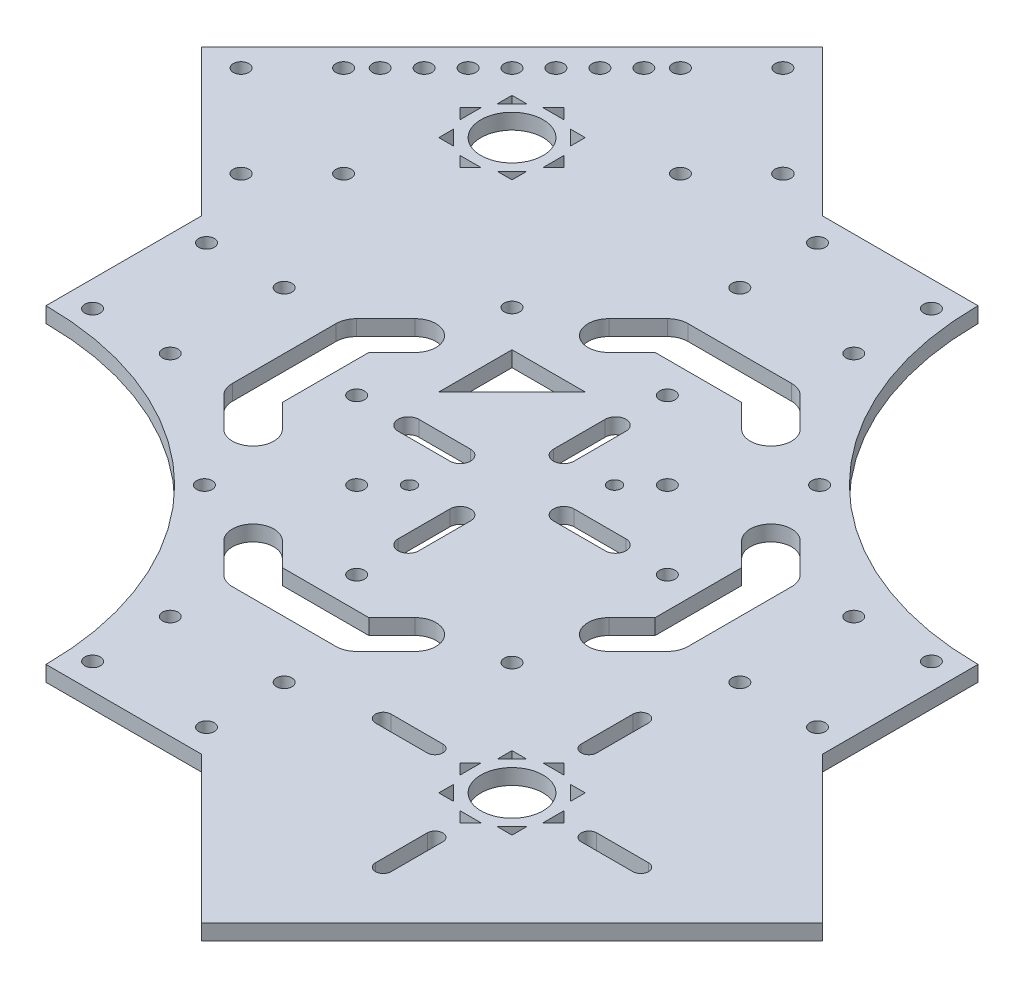
SolidWorks part; units mm, degrees
material "Hexcel AS4C (3000 丝)"
ref_plane "前视基准面" through (0, 0, 0) normal (0, 0, 1) x (1, 0, 0)
ref_plane "上视基准面" through (0, 0, 0) normal (0, 1, 0) x (1, 0, 0)
ref_plane "右视基准面" through (0, 0, 0) normal (1, 0, 0) x (0, 0, -1)
sketch "草图1" plane through (0, 0, 0) normal (0, 1, 0) x (1, 0, 0)
  line L0 (0, 0) -> (0, 75)
  line L1 (0, 0) -> (75, 0)
  line L2 (0, 0) -> (0, -75)
  line L3 (0, 0) -> (-75, 0)
  line L4 (0, 75) -> (15, 75)
  line L5 (0, 75) -> (-15, 75)
  line L6 (75, 0) -> (75, 15)
  line L7 (75, 0) -> (75, -15)
  line L8 (0, -75) -> (15, -75)
  line L9 (0, -75) -> (-15, -75)
  line L10 (-75, 0) -> (-75, -15)
  line L11 (-75, 0) -> (-75, 15)
  line L12 (75, 0) -> (70, 0)
  arc A0 (-75, 15) -> (-15, 75) centre (-75, 75) ccw
  arc A1 (15, 75) -> (75, 15) centre (75, 75) ccw
  arc A2 (75, -15) -> (15, -75) centre (75, -75) ccw
  arc A3 (-15, -75) -> (-75, -15) centre (-75, -75) ccw
  circle A4 centre (-11, 70) radius 1.25
  circle A5 centre (11, 70) radius 1.25
  circle A6 centre (70, -11) radius 1.25
  circle A7 centre (70, 11) radius 1.25
  circle A8 centre (-11, -70) radius 1.25
  circle A9 centre (11, -70) radius 1.25
  circle A10 centre (-70, 11) radius 1.25
  circle A11 centre (-70, -11) radius 1.25
  point P9 (0, 0)
  point P21 (0, 0)
  point P32 (0, 0)
  point P35 (0, 0)
  point P44 (0, 0)
  dimension "D1" = 4
extrude "凸台-拉伸1" add sketch "草图1" along normal blind 3 contours A2 L7 L1 L2 L8 A9 A6 | A3 L9 L2 L3 L10 A11 A8 | A0 L11 L3 L0 L5 A4 A10 | A1 L4 L0 L1 L6 A7 A5
sketch "草图2" plane through (0, 0, 0) normal (0, -1, 0) x (1, 0, 0)
  line L0 (0, 0) -> (-32.5736, -32.5736)
  line L1 (0, 0) -> (32.5736, -32.5736)
  line L2 (-31.4663, 0.3536) -> (-0.3536, 31.4663)
  line L3 (31.4663, -0.3536) -> (-0.3536, 31.4663)
  line L4 (0.3536, -31.4663) -> (31.4663, -0.3536)
  line L5 (0.3536, -31.4663) -> (-31.4663, 0.3536)
  arc A0 (-15, -75) -> (-75, -15) centre (-75, -75) ccw construction
  circle A2 centre (0.3536, -31.4663) radius 1.5
  circle A3 centre (31.4663, -0.3536) radius 1.5
  circle A4 centre (-0.3536, 31.4663) radius 1.5
  circle A5 centre (-31.4663, 0.3536) radius 1.5
  point P12 (-15.5563, -15.5563)
  point P16 (-15.9099, 15.9099)
  point P17 (15.9099, -15.9099)
extrude "切除-拉伸1" cut sketch "草图2" against normal blind 3 contours A3 | A2 | A5 | A4
sketch "草图3" plane through (0, 3, 0) normal (0, 1, 0) x (1, 0, 0)
  line L0 (0.3536, 31.4663) -> (-31.4663, -0.3536)
  line L1 (-15.5563, 15.5563) -> (-22.6274, 22.6274)
  line L2 (-15.5563, 15.5563) -> (-12.0208, 19.0919)
  line L3 (-15.5563, 15.5563) -> (-19.0919, 12.0208)
  line L4 (-19.0919, 12.0208) -> (-22.6274, 22.6274)
  line L5 (-12.0208, 19.0919) -> (-22.6274, 22.6274)
extrude "切除-拉伸2" cut sketch "草图3" against normal blind 3 contours L0 L5 L1 | L4 L0 L1
sketch "草图4" plane through (0, 3, 0) normal (0, 1, 0) x (1, 0, 0)
  line L0 (31.4663, 0.3536) -> (-0.3536, -31.4663)
  line L1 (0, 0) -> (21.2132, -21.2132)
  line L2 (28.2843, -14.1421) -> (14.1421, -28.2843)
  line L3 (14.1421, -28.2843) -> (28.2843, -14.1421) construction
  line L4 (8.4817, -22.6239) -> (22.6239, -8.4817)
  line L5 (19.8025, -33.9447) -> (33.9447, -19.8025)
  arc A0 (8.4817, -22.6239) -> (19.8025, -33.9447) centre (14.1421, -28.2843) ccw
  arc A1 (33.9447, -19.8025) -> (22.6239, -8.4817) centre (28.2843, -14.1421) ccw
  point P9 (21.2132, -21.2132)
extrude "切除-拉伸3" cut sketch "草图4" against normal blind 3
sketch "草图5" plane through (0, 3, 0) normal (0, 1, 0) x (1, 0, 0)
  line L0 (-12.0208, 19.0919) -> (-8.4853, 22.6274)
  line L1 (-8.4853, 22.6274) -> (-22.6274, 22.6274)
  line L2 (-19.0919, 12.0208) -> (-22.6274, 8.4853)
  line L3 (-22.6274, 8.4853) -> (-22.6274, 22.6274)
  line L4 (-12.0208, 19.0919) -> (-22.6274, 22.6274)
  line M28 (-19.0919, 12.0208) -> (-22.6274, 22.6274)
extrude "切除-拉伸4" cut sketch "草图5" against normal blind 10 contours L3 L2 M28 | L4 L0 L1
sketch "草图6" plane through (0, 3, 0) normal (0, 1, 0) x (1, 0, 0)
  line L0 (0, 0) -> (-28.2843, -28.2843)
  line L1 (-28.2843, -28.2843) -> (-35.3553, -21.2132)
  line L2 (0, 0) -> (-22.6274, 22.6274)
  circle A0 centre (-35.3553, -21.2132) radius 1.5
  circle A1 centre (-21.2132, -35.3553) radius 1.5
  circle A2 centre (35.3553, 21.2132) radius 1.5
  circle A3 centre (21.2132, 35.3553) radius 1.5
extrude "切除-拉伸5" cut sketch "草图6" against normal blind 10 contours A1 | A0 | A2 | A3
sketch "草图7" plane through (0, 3, 0) normal (0, 1, 0) x (1, 0, 0)
  circle A0 centre (-29.6985, 29.6985) radius 1.5
  circle A1 centre (29.6985, 29.6985) radius 1.5
  circle A2 centre (29.6985, -29.6985) radius 1.5
  circle A3 centre (-29.6985, -29.6985) radius 1.5
  point P11 (0, 0)
  dimension "D1" = 4
extrude "切除-拉伸8" cut sketch "草图7" against normal blind 10
sketch "草图8" plane through (0, 3, 0) normal (0, 1, 0) x (1, 0, 0)
  circle A0 centre (-11, 55) radius 1.5
  circle A1 centre (11, 55) radius 1.5
  circle A2 centre (55, 11) radius 1.5
  circle A3 centre (55, -11) radius 1.5
  circle A4 centre (11, -55) radius 1.5
  circle A5 centre (-11, -55) radius 1.5
  circle A6 centre (-55, -11) radius 1.5
  circle A7 centre (-55, 11) radius 1.5
  point P21 (0, 0)
  dimension "D1" = 4
extrude "切除-拉伸9" cut sketch "草图8" against normal blind 10
sketch "草图9" plane through (0, 3, 0) normal (0, 1, 0) x (1, 0, 0)
  circle A0 centre (0, 0) radius 15
extrude "切除-拉伸10" cut sketch "草图9" against normal blind 10
sketch "草图11" plane through (0, 3, 0) normal (0, 1, 0) x (1, 0, 0)
  circle A0 centre (-35.3553, -21.2132) radius 1.5
  circle A2 centre (35.3553, 21.2132) radius 1.5
  circle A3 centre (21.2132, 35.3553) radius 1.5
  circle A4 centre (0.3536, 31.4663) radius 1.5
  circle A5 centre (31.4663, 0.3536) radius 1.5
  circle A6 centre (-0.3536, -31.4663) radius 1.5
  circle A7 centre (-31.4663, -0.3536) radius 1.5
  circle A8 centre (-21.2132, -35.3553) radius 1.5
extrude "凸台-拉伸3" add sketch "草图11" against normal blind 3
sketch "草图12" plane through (0, 3, 0) normal (0, 1, 0) x (1, 0, 0)
  line L0 (0, 0) -> (-40, 0)
  line L1 (-40, 0) -> (-40, 10)
  line L2 (-40, 0) -> (-40, -10)
  line L3 (-40, -10) -> (-40, 10) construction
  line L4 (-44, -10) -> (-44, 10)
  line L5 (-36, -10) -> (-36, 10)
  line L6 (-10, 40) -> (10, 40) construction
  line L7 (-10, 44) -> (10, 44)
  line L8 (-10, 36) -> (10, 36)
  line L9 (40, 10) -> (40, -10) construction
  line L10 (44, 10) -> (44, -10)
  line L11 (36, 10) -> (36, -10)
  line L12 (10, -40) -> (-10, -40) construction
  line L13 (10, -44) -> (-10, -44)
  line L14 (10, -36) -> (-10, -36)
  arc A0 (-44, -10) -> (-36, -10) centre (-40, -10) ccw
  arc A1 (-36, 10) -> (-44, 10) centre (-40, 10) ccw
  arc A2 (-10, 44) -> (-10, 36) centre (-10, 40) ccw
  arc A3 (10, 36) -> (10, 44) centre (10, 40) ccw
  arc A4 (44, 10) -> (36, 10) centre (40, 10) ccw
  arc A5 (36, -10) -> (44, -10) centre (40, -10) ccw
  arc A6 (10, -44) -> (10, -36) centre (10, -40) ccw
  arc A7 (-10, -36) -> (-10, -44) centre (-10, -40) ccw
  point P3 (-40, 0)
  point P13 (0, 40)
  point P20 (40, 0)
  point P27 (0, -40)
  point P34 (0, 0)
  dimension "D1" = 4
extrude "切除-拉伸12" cut sketch "草图12" against normal blind 3
sketch "草图14" plane through (0, 3, 0) normal (0, 1, 0) x (1, 0, 0)
  line L0 (22.8277, -8.285) -> (8.285, -22.8277) construction
  line L1 (19.8025, -33.9447) -> (33.9447, -19.8025) construction
  line L2 (8.285, -22.8277) -> (22.8277, -8.285)
  line L3 (22.8277, -8.285) -> (19.8025, -33.9447)
  line L4 (19.8025, -33.9447) -> (33.9447, -19.8025)
  arc A0 (8.285, -22.8277) -> (19.8025, -33.9447) centre (14.1421, -28.2843) ccw
  arc A1 (8.285, -22.8277) -> (19.8025, -33.9447) centre (14.1421, -28.2843) ccw construction
  arc A2 (33.9447, -19.8025) -> (22.8277, -8.285) centre (28.2843, -14.1421) ccw construction
  arc A3 (22.8277, -8.285) -> (32.1857, -7.1522) centre (28.2843, -14.1421) ccw
  circle A4 centre (28.2843, -14.1421) radius 8.005
extrude "凸台-拉伸4" add sketch "草图14" against normal blind 3 contours A3 A4 L3 | L2 A3 L3 | A3 L2 A0 L3 | A3 L3 L4
sketch "草图15" plane through (0, 3, 0) normal (0, 1, 0) x (1, 0, 0)
  circle A0 centre (0, 0) radius 15
extrude "凸台-拉伸5" add sketch "草图15" against normal blind 3
sketch "草图17" plane through (0, 3, 0) normal (0, 1, 0) x (1, 0, 0)
  line L0 (0, 0) -> (0, -20)
  line L1 (0, -20) -> (0, -10) construction
  line L2 (-2, -20) -> (-2, -10)
  line L3 (2, -20) -> (2, -10)
  line L4 (-20, 0) -> (-10, 0) construction
  line L5 (-20, 2) -> (-10, 2)
  line L6 (-20, -2) -> (-10, -2)
  line L7 (0, 20) -> (0, 10) construction
  line L8 (2, 20) -> (2, 10)
  line L9 (-2, 20) -> (-2, 10)
  line L10 (20, 0) -> (10, 0) construction
  line L11 (20, -2) -> (10, -2)
  line L12 (20, 2) -> (10, 2)
  arc A0 (-2, -20) -> (2, -20) centre (0, -20) ccw
  arc A1 (2, -10) -> (-2, -10) centre (0, -10) ccw
  arc A2 (-20, 2) -> (-20, -2) centre (-20, 0) ccw
  arc A3 (-10, -2) -> (-10, 2) centre (-10, 0) ccw
  arc A4 (2, 20) -> (-2, 20) centre (0, 20) ccw
  arc A5 (-2, 10) -> (2, 10) centre (0, 10) ccw
  arc A6 (20, -2) -> (20, 2) centre (20, 0) ccw
  arc A7 (10, 2) -> (10, -2) centre (10, 0) ccw
  point P3 (0, -15)
  point P13 (-15, 0)
  point P20 (0, 15)
  point P27 (15, 0)
  point P33 (0, 0)
  dimension "D1" = 4
extrude "切除-拉伸13" cut sketch "草图17" against normal blind 3 contours L8 A5 L9 A4 | L12 A7 L11 A6 | L3 A1 L2 A0 | L5 A3 L6 A2
sketch "草图18" plane through (0, 3, 0) normal (0, 1, 0) x (1, 0, 0)
  line L0 (0, 0) -> (-32.5736, 32.5736)
  line L1 (-32.5736, 32.5736) -> (-46.7157, 46.7157)
  line L2 (-50.2513, 50.2513) -> (-61.9773, 38.5252)
  line L3 (-46.7157, 46.7157) -> (-50.2513, 50.2513)
  line L4 (-61.9773, 38.5252) -> (-38.5252, 61.9773)
  line L5 (-38.5252, 61.9773) -> (-22.5002, 45.9523)
  line L6 (-61.9773, 38.5252) -> (-45.9523, 22.5002)
  arc A0 (-75, 15) -> (-15, 75) centre (-75, 75) ccw construction
  circle A1 centre (-67.9289, 67.9289) radius 30
  circle A2 centre (-75, 75) radius 60
extrude "凸台-拉伸7" add sketch "草图18" against normal blind 3 contours L4 A1 L2 | L2 A1 L3 | L3 A1 L4 | L6 A2 L1 A1 | L1 A2 L5 A1
sketch "草图19" plane through (0, 3, 0) normal (0, 1, 0) x (1, 0, 0)
  line L0 (-61.9773, 38.5252) -> (-38.5252, 61.9773)
  line L1 (-50.2513, 50.2513) -> (-36.1091, 36.1091)
  line L2 (-36.1091, 36.1091) -> (-43.1802, 29.0381)
  line L3 (-36.1091, 36.1091) -> (-29.0381, 43.1802)
  line L4 (-29.0381, 43.1802) -> (-37.1408, 51.2829)
  line L5 (-37.1408, 51.2829) -> (-51.2829, 37.1408)
  line L6 (-51.2829, 37.1408) -> (-43.1802, 29.0381)
  circle A1 centre (-67.9289, 67.9289) radius 35
  circle A2 centre (-67.9289, 67.9289) radius 45
extrude "切除-拉伸14" cut sketch "草图19" against normal blind 3 contours L1 A2 L4 A1 | L6 A2 L1 A1
sketch "草图21" plane through (0, 3, 0) normal (0, 1, 0) x (1, 0, 0)
  line L0 (-61.9773, 38.5252) -> (-38.5252, 61.9773)
  line L1 (-67.9289, 67.9289) -> (-53.7868, 53.7868)
  line L2 (-82.0711, 82.0711) -> (-75, 75)
  line L3 (-67.9289, 67.9289) -> (-82.0711, 82.0711)
  line L4 (-53.7868, 53.7868) -> (-60.8579, 60.8579)
  line L5 (-82.0711, 82.0711) -> (-75, 75) construction
  line L6 (-81.1872, 82.955) -> (-74.1161, 75.8839)
  line L7 (-82.955, 81.1872) -> (-75.8839, 74.1161)
  line L8 (-60.8579, 60.8579) -> (-53.7868, 53.7868) construction
  line L9 (-59.974, 61.7417) -> (-52.9029, 54.6707)
  line L10 (-61.7417, 59.974) -> (-54.6707, 52.9029)
  arc A0 (-81.1872, 82.955) -> (-82.955, 81.1872) centre (-82.0711, 82.0711) ccw
  arc A1 (-75.8839, 74.1161) -> (-74.1161, 75.8839) centre (-75, 75) ccw
  arc A2 (-59.974, 61.7417) -> (-61.7417, 59.974) centre (-60.8579, 60.8579) ccw
  arc A3 (-54.6707, 52.9029) -> (-52.9029, 54.6707) centre (-53.7868, 53.7868) ccw
  point P2 (-78.5355, 78.5355)
  point P15 (-57.3223, 57.3223)
extrude "切除-拉伸15" cut sketch "草图21" against normal blind 3
pattern_circular "阵列(圆周)1" count 8 over 360 about axis through (-67.9289, 0, -67.9289) along (0, 1, 0) of "切除-拉伸15"
sketch "草图22" plane through (0, 3, 0) normal (0, 1, 0) x (1, 0, 0)
  line L0 (0, 0) -> (9.8995, 9.8995)
  line L1 (0, 0) -> (-9.8995, -9.8995)
  circle A0 centre (9.8995, 9.8995) radius 1.25
  circle A1 centre (-9.8995, -9.8995) radius 1.25
extrude "切除-拉伸17" cut sketch "草图22" against normal blind 3 contours A0 | A1
sketch "草图23" plane through (0, 3, 0) normal (0, 1, 0) x (1, 0, 0)
  circle A0 centre (0, 30) radius 1.5
  circle A1 centre (30, 0) radius 1.5
  circle A2 centre (0, -30) radius 1.5
  circle A3 centre (-30, 0) radius 1.5
  point P13 (0, 0)
  dimension "D1" = 4
extrude "切除-拉伸18" cut sketch "草图23" against normal blind 10
sketch "草图24" plane through (0, 3, 0) normal (0, 1, 0) x (1, 0, 0)
  circle A0 centre (-15, -15) radius 1.5
  circle A1 centre (15, 15) radius 1.5
extrude "切除-拉伸19" cut sketch "草图24" against normal blind 10
sketch "草图25" plane through (0, 3, 0) normal (0, 1, 0) x (1, 0, 0)
  circle A0 centre (-75, 75) radius 60
extrude "切除-拉伸20" cut sketch "草图25" against normal blind 10
sketch "草图26" plane through (0, 3, 0) normal (0, 1, 0) x (1, 0, 0)
  line L0 (-15, 75) -> (-75, 15)
  circle A0 centre (-75, 75) radius 60
extrude "凸台-拉伸8" add sketch "草图26" against normal blind 3 contours L0 A0
sketch "草图27" plane through (0, 0, 0) normal (0, -1, 0) x (1, 0, 0)
  line L0 (-45, -45) -> (-23.5998, -66.4002)
  line L1 (-15, -75) -> (-75, -15) construction
  line L2 (-23.5998, -66.4002) -> (-66.0262, -23.9738)
  line L3 (-15, -75) -> (-22.0711, -82.0711)
  line L4 (-22.0711, -82.0711) -> (-75, -15)
  line L5 (-75, -15) -> (-82.0711, -22.0711)
  line L6 (-82.0711, -22.0711) -> (-22.0711, -82.0711)
  line L7 (75, 15) -> (15, 75)
  line L8 (15, 75) -> (22.0711, 82.0711)
  line L9 (75, 15) -> (82.0711, 22.0711)
  line L10 (82.0711, 22.0711) -> (22.0711, 82.0711)
  line L11 (-15, -75) -> (-75, -15)
  line L12 (-22.0711, -82.0711) -> (-29.1421, -89.1421)
  line L13 (-29.1421, -89.1421) -> (-82.0711, -22.0711)
  line L14 (-82.0711, -22.0711) -> (-89.1421, -29.1421)
  line L15 (-89.1421, -29.1421) -> (-29.1421, -89.1421)
  circle A0 centre (75, 75) radius 60
extrude "凸台-拉伸10" add sketch "草图27" against normal blind 3 contours L14 L15 L13 | L13 L12 L6 | L5 L6 L4 | L3 L11 L0 L2 L4
sketch "草图28" plane through (0, 0, 0) normal (0, -1, 0) x (1, 0, 0)
  line L0 (-59.1421, -59.1421) -> (-52.0711, -52.0711)
  line L1 (-89.1421, -29.1421) -> (-29.1421, -89.1421) construction
  line L2 (-52.0711, -52.0711) -> (-25.9081, -78.234)
  line L3 (-52.0711, -52.0711) -> (-78.234, -25.9081)
  line L4 (11, -70) -> (8.198, -68.4493)
  circle A1 centre (11, -70) radius 1.5
  circle A2 centre (-11, -70) radius 1.5
  circle A3 centre (-70, -11) radius 1.5
  circle A4 centre (-70, 11) radius 1.5
  circle A5 centre (-11, 70) radius 1.5
  circle A6 centre (11, 70) radius 1.5
  circle A7 centre (70, 11) radius 1.5
  circle A8 centre (70, -11) radius 1.5
  circle A9 centre (-25.9081, -78.234) radius 1.54
  circle A10 centre (-78.234, -25.9081) radius 1.52
extrude "切除-拉伸21" cut sketch "草图28" against normal blind 3
sketch "草图29" plane through (0, 0, 0) normal (0, -1, 0) x (1, 0, 0)
  line L0 (-59.1421, -59.1421) -> (-22.6274, -22.6274)
  line L1 (-78.234, -25.9081) -> (-68.3345, -35.8076)
  line L2 (-89.1421, -29.1421) -> (-29.1421, -89.1421) construction
  circle A0 centre (-68.3345, -35.8076) radius 1.5
  circle A1 centre (-35.8076, -68.3345) radius 1.5
extrude "切除-拉伸22" cut sketch "草图29" against normal blind 3 contours A1 | A0
sketch "草图30" plane through (0, 0, 0) normal (0, -1, 0) x (1, 0, 0)
  line L0 (-29.1421, -89.1421) -> (-89.1421, -29.1421)
  line L1 (-29.1421, -89.1421) -> (-43.2843, -103.2843)
  line L2 (-89.1421, -29.1421) -> (-103.2843, -43.2843)
  line L3 (-43.2843, -103.2843) -> (-103.2843, -43.2843)
extrude "凸台-拉伸11" add sketch "草图30" against normal blind 3
sketch "草图31" plane through (0, 0, 0) normal (0, -1, 0) x (1, 0, 0)
  line L1 (-25.9081, -78.234) -> (-78.234, -25.9081)
  circle A0 centre (-43.5858, -95.9117) radius 1.5
  circle A1 centre (-53.4853, -86.0122) radius 1.5
  circle A2 centre (-86.0122, -53.4853) radius 1.5
  circle A3 centre (-95.9117, -43.5858) radius 1.5
extrude "切除-拉伸23" cut sketch "草图31" against normal blind 3 contours A0 | A1 | A2 | A3
sketch "草图32" plane through (0, 0, 0) normal (0, -1, 0) x (1, 0, 0)
  line L0 (75, 15) -> (15, 75)
  line L1 (75, 15) -> (15, 75)
  line L2 (75, 15) -> (89.1421, 29.1421)
  line L3 (15, 75) -> (29.1421, 89.1421)
  line L4 (89.1421, 29.1421) -> (29.1421, 89.1421)
  circle A0 centre (75, 75) radius 60
extrude "凸台-拉伸12" add sketch "草图32" against normal blind 3 contours L0 A0 | L2 L4 L3 L0
sketch "草图33" plane through (0, 0, 0) normal (0, -1, 0) x (-1, 0, 0)
  line L0 (-29.6985, -29.6985) -> (-59.1421, -59.1421)
  line L1 (-89.1421, -29.1421) -> (-29.1421, -89.1421) construction
  line L2 (-44.4203, -44.4203) -> (-14.6894, -44.4203)
  line L3 (-14.6894, -44.4203) -> (-44.4203, -16.8394)
  line L4 (-44.4203, -16.8394) -> (-44.4203, -44.4203)
  line L5 (-29.5549, -44.4203) -> (-19.5549, -44.4203) construction
  line L6 (-29.5549, -42.92) -> (-19.5549, -42.92)
  line L7 (-29.5549, -45.9207) -> (-19.5549, -45.9207)
  line L8 (-44.4203, -59.2858) -> (-44.4203, -69.2858) construction
  line L9 (-42.92, -59.2858) -> (-42.92, -69.2858)
  line L10 (-45.9207, -59.2858) -> (-45.9207, -69.2858)
  line L11 (-59.2858, -44.4203) -> (-69.2858, -44.4203) construction
  line L12 (-59.2858, -45.9207) -> (-69.2858, -45.9207)
  line L13 (-59.2858, -42.92) -> (-69.2858, -42.92)
  line L14 (-44.4203, -29.5549) -> (-44.4203, -19.5549) construction
  line L15 (-45.9207, -29.5549) -> (-45.9207, -19.5549)
  line L16 (-42.92, -29.5549) -> (-42.92, -19.5549)
  arc A0 (-29.5549, -42.92) -> (-29.5549, -45.9207) centre (-29.5549, -44.4203) ccw
  arc A1 (-19.5549, -45.9207) -> (-19.5549, -42.92) centre (-19.5549, -44.4203) ccw
  arc A2 (-42.92, -59.2858) -> (-45.9207, -59.2858) centre (-44.4203, -59.2858) ccw
  arc A3 (-45.9207, -69.2858) -> (-42.92, -69.2858) centre (-44.4203, -69.2858) ccw
  arc A4 (-59.2858, -45.9207) -> (-59.2858, -42.92) centre (-59.2858, -44.4203) ccw
  arc A5 (-69.2858, -42.92) -> (-69.2858, -45.9207) centre (-69.2858, -44.4203) ccw
  arc A6 (-45.9207, -29.5549) -> (-42.92, -29.5549) centre (-44.4203, -29.5549) ccw
  arc A7 (-42.92, -19.5549) -> (-45.9207, -19.5549) centre (-44.4203, -19.5549) ccw
  point P10 (-24.5549, -44.4203)
  point P20 (-44.4203, -64.2858)
  point P27 (-64.2858, -44.4203)
  point P34 (-44.4203, -24.5549)
  point P39 (-44.4203, -44.4203)
  dimension "D1" = 4
extrude "切除-拉伸24" cut sketch "草图33" against normal blind 3 contours L10 A3 L9 A2 | L7 A1 L6 A0 | L12 A5 L13 A4 | L15 A7 L16 A6
sketch "草图34" plane through (0, 0, 0) normal (0, -1, 0) x (1, 0, 0)
  line L0 (29.1421, 89.1421) -> (89.1421, 29.1421)
  line L1 (29.1421, 89.1421) -> (43.2843, 103.2843)
  line L2 (89.1421, 29.1421) -> (103.2843, 43.2843)
  line L3 (43.2843, 103.2843) -> (103.2843, 43.2843)
  line L4 (75, 15) -> (89.1421, 29.1421) construction
  line L5 (89.1421, 29.1421) -> (29.1421, 89.1421) construction
extrude "凸台-拉伸13" add sketch "草图34" against normal blind 3
sketch "草图35" plane through (0, 0, 0) normal (0, -1, 0) x (1, 0, 0)
  line L0 (10, 40) -> (15.6569, 34.3431)
  line L1 (10, 40) -> (15.6569, 34.3431) construction
  line L2 (12.8284, 42.8284) -> (18.4853, 37.1716)
  line L3 (7.1716, 37.1716) -> (12.8284, 31.5147)
  line L4 (-10, 40) -> (-15.6569, 34.3431) construction
  line L5 (-7.1716, 37.1716) -> (-12.8284, 31.5147)
  line L6 (-12.8284, 42.8284) -> (-18.4853, 37.1716)
  line L7 (40, -10) -> (34.3431, -15.6569) construction
  line L8 (42.8284, -12.8284) -> (37.1716, -18.4853)
  line L9 (37.1716, -7.1716) -> (31.5147, -12.8284)
  line L10 (40, 10) -> (34.3431, 15.6569) construction
  line L11 (37.1716, 7.1716) -> (31.5147, 12.8284)
  line L12 (42.8284, 12.8284) -> (37.1716, 18.4853)
  line L13 (-10, -40) -> (-15.6569, -34.3431) construction
  line L14 (-12.8284, -42.8284) -> (-18.4853, -37.1716)
  line L15 (-7.1716, -37.1716) -> (-12.8284, -31.5147)
  line L16 (10, -40) -> (15.6569, -34.3431) construction
  line L17 (7.1716, -37.1716) -> (12.8284, -31.5147)
  line L18 (12.8284, -42.8284) -> (18.4853, -37.1716)
  line L19 (-40, 10) -> (-34.3431, 15.6569) construction
  line L20 (-42.8284, 12.8284) -> (-37.1716, 18.4853)
  line L21 (-37.1716, 7.1716) -> (-31.5147, 12.8284)
  line L22 (-40, -10) -> (-34.3431, -15.6569) construction
  line L23 (-37.1716, -7.1716) -> (-31.5147, -12.8284)
  line L24 (-42.8284, -12.8284) -> (-37.1716, -18.4853)
  arc A0 (12.8284, 42.8284) -> (7.1716, 37.1716) centre (10, 40) ccw
  arc A1 (12.8284, 31.5147) -> (18.4853, 37.1716) centre (15.6569, 34.3431) ccw
  arc A2 (-7.1716, 37.1716) -> (-12.8284, 42.8284) centre (-10, 40) ccw
  arc A3 (-18.4853, 37.1716) -> (-12.8284, 31.5147) centre (-15.6569, 34.3431) ccw
  arc A4 (42.8284, -12.8284) -> (37.1716, -7.1716) centre (40, -10) ccw
  arc A5 (31.5147, -12.8284) -> (37.1716, -18.4853) centre (34.3431, -15.6569) ccw
  arc A6 (37.1716, 7.1716) -> (42.8284, 12.8284) centre (40, 10) ccw
  arc A7 (37.1716, 18.4853) -> (31.5147, 12.8284) centre (34.3431, 15.6569) ccw
  arc A8 (-12.8284, -42.8284) -> (-7.1716, -37.1716) centre (-10, -40) ccw
  arc A9 (-12.8284, -31.5147) -> (-18.4853, -37.1716) centre (-15.6569, -34.3431) ccw
  arc A10 (7.1716, -37.1716) -> (12.8284, -42.8284) centre (10, -40) ccw
  arc A11 (18.4853, -37.1716) -> (12.8284, -31.5147) centre (15.6569, -34.3431) ccw
  arc A12 (-42.8284, 12.8284) -> (-37.1716, 7.1716) centre (-40, 10) ccw
  arc A13 (-31.5147, 12.8284) -> (-37.1716, 18.4853) centre (-34.3431, 15.6569) ccw
  arc A14 (-37.1716, -7.1716) -> (-42.8284, -12.8284) centre (-40, -10) ccw
  arc A15 (-37.1716, -18.4853) -> (-31.5147, -12.8284) centre (-34.3431, -15.6569) ccw
  point P3 (12.8284, 37.1716)
  point P11 (-12.8284, 37.1716)
  point P21 (37.1716, -12.8284)
  point P28 (37.1716, 12.8284)
  point P35 (-12.8284, -37.1716)
  point P42 (12.8284, -37.1716)
  point P49 (-37.1716, 12.8284)
  point P56 (-37.1716, -12.8284)
  point P61 (0, 0)
  dimension "D1" = 4
extrude "切除-拉伸25" cut sketch "草图35" against normal blind 10
sketch "草图36" plane through (0, 0, 0) normal (0, -1, 0) x (1, 0, 0)
  line L0 (19.5549, 44.4203) -> (29.5549, 44.4203) construction
  line L1 (19.5549, 45.9203) -> (29.5549, 45.9203)
  line L2 (19.5549, 42.9203) -> (29.5549, 42.9203)
  line L3 (26.6259, 51.4914) -> (36.6259, 51.4914) construction
  line L4 (44.4203, 69.2858) -> (44.4203, 59.2858) construction
  line L5 (45.9203, 69.2858) -> (45.9203, 59.2858)
  line L6 (42.9203, 69.2858) -> (42.9203, 59.2858)
  line L7 (69.2858, 44.4203) -> (59.2858, 44.4203) construction
  line L8 (69.2858, 42.9203) -> (59.2858, 42.9203)
  line L9 (69.2858, 45.9203) -> (59.2858, 45.9203)
  line L10 (44.4203, 19.5549) -> (44.4203, 29.5549) construction
  line L11 (42.9203, 19.5549) -> (42.9203, 29.5549)
  line L12 (45.9203, 19.5549) -> (45.9203, 29.5549)
  line L13 (26.6259, 52.9914) -> (36.6259, 52.9914)
  line L14 (26.6259, 49.9914) -> (36.6259, 49.9914)
  line L15 (51.4914, 76.3568) -> (51.4914, 66.3568) construction
  line L16 (52.9914, 76.3568) -> (52.9914, 66.3568)
  line L17 (49.9914, 76.3568) -> (49.9914, 66.3568)
  line L18 (76.3568, 51.4914) -> (66.3568, 51.4914) construction
  line L19 (76.3568, 49.9914) -> (66.3568, 49.9914)
  line L20 (76.3568, 52.9914) -> (66.3568, 52.9914)
  line L21 (51.4914, 26.6259) -> (51.4914, 36.6259) construction
  line L22 (49.9914, 26.6259) -> (49.9914, 36.6259)
  line L23 (52.9914, 26.6259) -> (52.9914, 36.6259)
  arc A0 (19.5549, 45.9203) -> (19.5549, 42.9203) centre (19.5549, 44.4203) ccw
  arc A1 (29.5549, 42.9203) -> (29.5549, 45.9203) centre (29.5549, 44.4203) ccw
  arc A2 (45.9203, 69.2858) -> (42.9203, 69.2858) centre (44.4203, 69.2858) ccw
  arc A3 (42.9203, 59.2858) -> (45.9203, 59.2858) centre (44.4203, 59.2858) ccw
  arc A4 (69.2858, 42.9203) -> (69.2858, 45.9203) centre (69.2858, 44.4203) ccw
  arc A5 (59.2858, 45.9203) -> (59.2858, 42.9203) centre (59.2858, 44.4203) ccw
  arc A6 (42.9203, 19.5549) -> (45.9203, 19.5549) centre (44.4203, 19.5549) ccw
  arc A7 (45.9203, 29.5549) -> (42.9203, 29.5549) centre (44.4203, 29.5549) ccw
  arc A8 (26.6259, 52.9914) -> (26.6259, 49.9914) centre (26.6259, 51.4914) ccw
  arc A9 (36.6259, 49.9914) -> (36.6259, 52.9914) centre (36.6259, 51.4914) ccw
  arc A10 (52.9914, 76.3568) -> (49.9914, 76.3568) centre (51.4914, 76.3568) ccw
  arc A11 (49.9914, 66.3568) -> (52.9914, 66.3568) centre (51.4914, 66.3568) ccw
  arc A12 (76.3568, 49.9914) -> (76.3568, 52.9914) centre (76.3568, 51.4914) ccw
  arc A13 (66.3568, 52.9914) -> (66.3568, 49.9914) centre (66.3568, 51.4914) ccw
  arc A14 (49.9914, 26.6259) -> (52.9914, 26.6259) centre (51.4914, 26.6259) ccw
  arc A15 (52.9914, 36.6259) -> (49.9914, 36.6259) centre (51.4914, 36.6259) ccw
  point P4 (24.5549, 44.4203)
  point P13 (31.6259, 51.4914)
  point P19 (44.4203, 64.2858)
  point P26 (64.2858, 44.4203)
  point P33 (44.4203, 24.5549)
  point P41 (51.4914, 71.3568)
  point P48 (71.3568, 51.4914)
  point P55 (51.4914, 31.6259)
  dimension "D1" = 2
extrude "切除-拉伸26" cut sketch "草图36" against normal blind 10
sketch "草图37" plane through (0, 0, 0) normal (0, -1, 0) x (1, 0, 0)
  line L0 (44.4203, 69.2858) -> (44.4203, 59.8535) construction
  line L1 (47.888, 69.2858) -> (47.888, 59.8535)
  line L2 (40.9527, 69.2858) -> (40.9527, 59.8535)
  line L3 (60.035, 44.7696) -> (68.5031, 44.7696) construction
  line L4 (60.035, 48.1814) -> (68.5031, 48.1814)
  line L5 (60.035, 41.3579) -> (68.5031, 41.3579)
  line L6 (44.4203, 29.5549) -> (44.4203, 19.6289) construction
  line L7 (48.5122, 29.5549) -> (48.5122, 19.6289)
  line L8 (40.3284, 29.5549) -> (40.3284, 19.6289)
  line L9 (20.3241, 44.7696) -> (29.5195, 44.7696) construction
  line L10 (20.3241, 48.0853) -> (29.5195, 48.0853)
  line L11 (20.3241, 41.454) -> (29.5195, 41.454)
  arc A0 (47.888, 69.2858) -> (40.9527, 69.2858) centre (44.4203, 69.2858) ccw
  arc A1 (40.9527, 59.8535) -> (47.888, 59.8535) centre (44.4203, 59.8535) ccw
  arc A2 (60.035, 48.1814) -> (60.035, 41.3579) centre (60.035, 44.7696) ccw
  arc A3 (68.5031, 41.3579) -> (68.5031, 48.1814) centre (68.5031, 44.7696) ccw
  arc A4 (48.5122, 29.5549) -> (40.3284, 29.5549) centre (44.4203, 29.5549) ccw
  arc A5 (40.3284, 19.6289) -> (48.5122, 19.6289) centre (44.4203, 19.6289) ccw
  arc A6 (20.3241, 48.0853) -> (20.3241, 41.454) centre (20.3241, 44.7696) ccw
  arc A7 (29.5195, 41.454) -> (29.5195, 48.0853) centre (29.5195, 44.7696) ccw
  point P3 (44.4203, 64.5696)
  point P8 (64.2691, 44.7696)
  point P15 (44.4203, 24.5919)
  point P23 (24.9218, 44.7696)
extrude "凸台-拉伸14" add sketch "草图37" against normal blind 3
sketch "草图38" plane through (0, 0, 0) normal (0, -1, 0) x (1, 0, 0)
  line L0 (-52.4533, -52.4533) -> (-53.8675, -51.0391)
  line L1 (-51.0391, -53.8675) -> (-52.4533, -52.4533)
  line L2 (57.1482, 57.1482) -> (55.734, 58.5624)
  line L3 (-53.8675, -51.0391) -> (-51.0391, -51.0391)
  line L4 (-51.0391, -53.8675) -> (-51.0391, -51.0391)
  line L5 (58.5624, 55.734) -> (57.1482, 57.1482)
  line L6 (55.734, 58.5624) -> (58.5624, 58.5624)
  line L7 (58.5624, 55.734) -> (58.5624, 58.5624)
  line L8 (59.4914, 53.4914) -> (61.4914, 51.4914)
  line L9 (59.4914, 49.4914) -> (61.4914, 51.4914)
  line L10 (59.4914, 49.4914) -> (59.4914, 51.4914)
  line L11 (59.4914, 51.4914) -> (59.4914, 53.4914)
  line L12 (58.5624, 47.2487) -> (58.5624, 44.4203)
  line L13 (55.734, 44.4203) -> (58.5624, 44.4203)
  line L14 (55.734, 44.4203) -> (57.1482, 45.8345)
  line L15 (57.1482, 45.8345) -> (58.5624, 47.2487)
  line L16 (53.4914, 43.4914) -> (51.4914, 41.4914)
  line L17 (49.4914, 43.4914) -> (51.4914, 41.4914)
  line L18 (49.4914, 43.4914) -> (51.4914, 43.4914)
  line L19 (51.4914, 43.4914) -> (53.4914, 43.4914)
  line L20 (47.2487, 44.4203) -> (44.4203, 44.4203)
  line L21 (44.4203, 47.2487) -> (44.4203, 44.4203)
  line L22 (44.4203, 47.2487) -> (45.8345, 45.8345)
  line L23 (45.8345, 45.8345) -> (47.2487, 44.4203)
  line L24 (43.4914, 49.4914) -> (41.4914, 51.4914)
  line L25 (43.4914, 53.4914) -> (41.4914, 51.4914)
  line L26 (43.4914, 53.4914) -> (43.4914, 51.4914)
  line L27 (43.4914, 51.4914) -> (43.4914, 49.4914)
  line L28 (44.4203, 55.734) -> (44.4203, 58.5624)
  line L29 (47.2487, 58.5624) -> (44.4203, 58.5624)
  line L30 (47.2487, 58.5624) -> (45.8345, 57.1482)
  line L31 (45.8345, 57.1482) -> (44.4203, 55.734)
  line L32 (49.4914, 59.4914) -> (51.4914, 61.4914)
  line L33 (53.4914, 59.4914) -> (51.4914, 61.4914)
  line L34 (53.4914, 59.4914) -> (51.4914, 59.4914)
  line L35 (51.4914, 59.4914) -> (49.4914, 59.4914)
  line L36 (-50.1102, -56.1102) -> (-48.1102, -58.1102)
  line L37 (-50.1102, -60.1102) -> (-48.1102, -58.1102)
  line L38 (-50.1102, -60.1102) -> (-50.1102, -58.1102)
  line L39 (-50.1102, -58.1102) -> (-50.1102, -56.1102)
  line L40 (-51.0391, -62.3528) -> (-51.0391, -65.1812)
  line L41 (-53.8675, -65.1812) -> (-51.0391, -65.1812)
  line L42 (-53.8675, -65.1812) -> (-52.4533, -63.767)
  line L43 (-52.4533, -63.767) -> (-51.0391, -62.3528)
  line L44 (-56.1102, -66.1102) -> (-58.1102, -68.1102)
  line L45 (-60.1102, -66.1102) -> (-58.1102, -68.1102)
  line L46 (-60.1102, -66.1102) -> (-58.1102, -66.1102)
  line L47 (-58.1102, -66.1102) -> (-56.1102, -66.1102)
  line L48 (-62.3528, -65.1812) -> (-65.1812, -65.1812)
  line L49 (-65.1812, -62.3528) -> (-65.1812, -65.1812)
  line L50 (-65.1812, -62.3528) -> (-63.767, -63.767)
  line L51 (-63.767, -63.767) -> (-62.3528, -65.1812)
  line L52 (-66.1102, -60.1102) -> (-68.1102, -58.1102)
  line L53 (-66.1102, -56.1102) -> (-68.1102, -58.1102)
  line L54 (-66.1102, -56.1102) -> (-66.1102, -58.1102)
  line L55 (-66.1102, -58.1102) -> (-66.1102, -60.1102)
  line L56 (-65.1812, -53.8675) -> (-65.1812, -51.0391)
  line L57 (-62.3528, -51.0391) -> (-65.1812, -51.0391)
  line L58 (-62.3528, -51.0391) -> (-63.767, -52.4533)
  line L59 (-63.767, -52.4533) -> (-65.1812, -53.8675)
  line L60 (-60.1102, -50.1102) -> (-58.1102, -48.1102)
  line L61 (-56.1102, -50.1102) -> (-58.1102, -48.1102)
  line L62 (-56.1102, -50.1102) -> (-58.1102, -50.1102)
  line L63 (-58.1102, -50.1102) -> (-60.1102, -50.1102)
  circle A0 centre (51.4914, 51.4914) radius 6
  circle A1 centre (-58.1102, -58.1102) radius 6
  point P40 (51.4914, 51.4914)
  point P70 (-58.1102, -58.1102)
  dimension "D1" = 2
extrude "切除-拉伸28" cut sketch "草图38" against normal blind 3
sketch "草图39" plane through (0, 0, 0) normal (0, -1, 0) x (1, 0, 0)
  circle A0 centre (-69.7487, -69.7487) radius 1.5
  circle A1 centre (-73.9914, -65.5061) radius 1.5
  circle A2 centre (-78.234, -61.2635) radius 1.5
  circle A3 centre (-82.4767, -57.0208) radius 1.5
  circle A4 centre (-65.5061, -73.9914) radius 1.5
  circle A5 centre (-61.2635, -78.234) radius 1.5
  circle A6 centre (-57.0208, -82.4767) radius 1.5
extrude "切除-拉伸29" cut sketch "草图39" against normal blind 3
